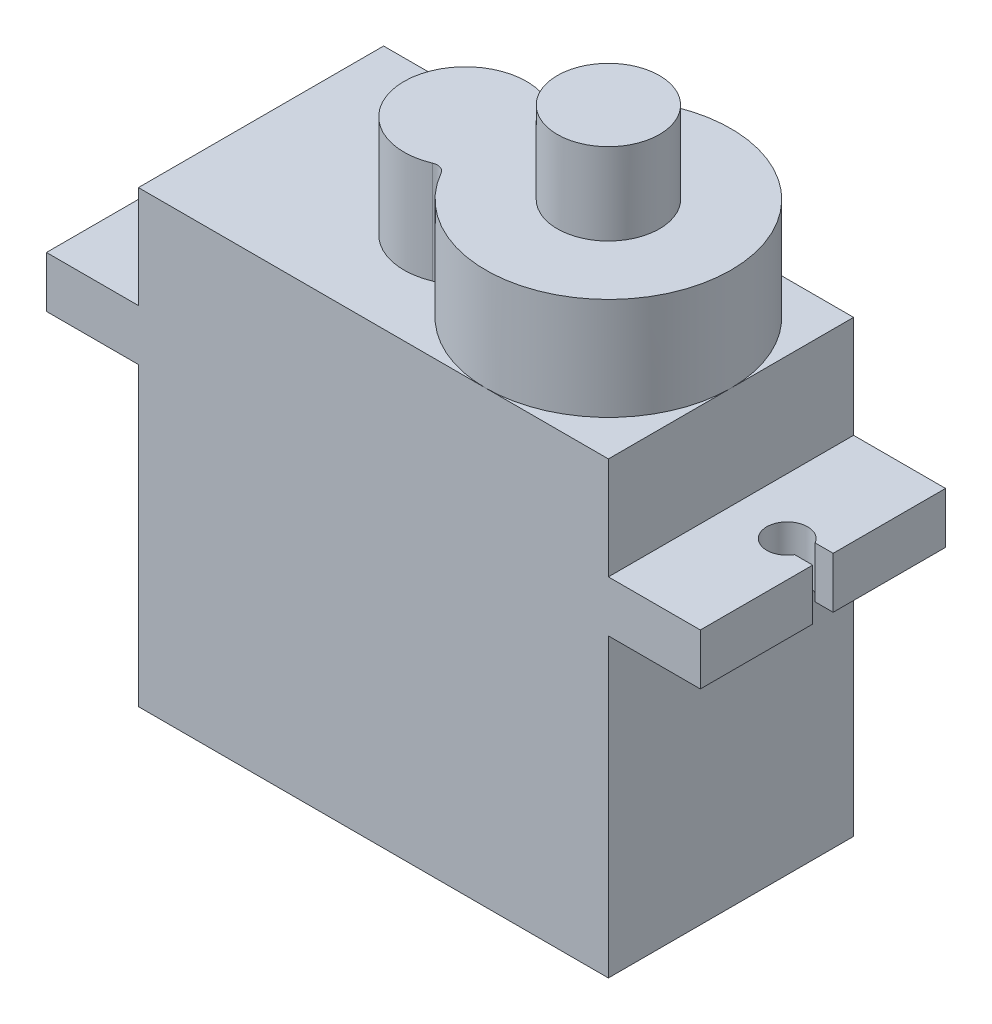
SolidWorks part; units mm, degrees
ref_plane "前视基准面" through (0, 0, 0) normal (0, 0, 1) x (1, 0, 0)
ref_plane "上视基准面" through (0, 0, 0) normal (0, 1, 0) x (1, 0, 0)
ref_plane "右视基准面" through (0, 0, 0) normal (1, 0, 0) x (0, 0, -1)
sketch "草图1" plane through (0, 0, 0) normal (0, 1, 0) x (1, 0, 0)
  line L1 (-11.5, -6) -> (11.5, -6)
  line L2 (-11.5, -6) -> (-11.5, 6)
  line L3 (-11.5, 6) -> (11.5, 6)
  line L4 (11.5, -6) -> (11.5, 6)
  line L5 (0, 6) -> (0, -6) construction
  line L6 (-11.5, 0) -> (11.5, 0) construction
  point P0 (0, 0)
  dimension "D1" = 12
  dimension "D2" = 23
extrude "凸台-拉伸1" add sketch "草图1" along normal blind 22
ref_plane "基准面1" through (0, 17, 0) normal (0, 1, 0) x (1, 0, 0)
sketch "草图2" plane through (0, 17, 0) normal (0, 1, 0) x (1, 0, 0)
  line L0 (-11.5, -6) -> (11.5, -6) construction
  line L1 (-16, -6) -> (16, -6)
  line L2 (-16, -6) -> (-16, 6)
  line L3 (-16, 6) -> (16, 6)
  line L4 (16, -6) -> (16, 6)
  line L5 (0, 6) -> (0, -6) construction
  line L6 (-16, 0) -> (16, 0) construction
  point P0 (0, 0)
  dimension "D1" = 32
extrude "凸台-拉伸2" add sketch "草图2" against normal blind 2.5
sketch "草图3" plane through (0, 17, 0) normal (0, 1, 0) x (1, 0, 0)
  line L0 (-16, 6) -> (-16, -6) construction
  line L1 (-16, 0.5) -> (-15.116, 0.5)
  line L2 (-16, 0.5) -> (-16, -0.5)
  line L3 (-16, -0.5) -> (-15.116, -0.5)
  line L5 (-15.558, -0.5) -> (-15.558, 0.5) construction
  line L6 (-16, 0) -> (-15.558, 0) construction
  arc A0 (-15.116, -0.5) -> (-15.116, 0.5) centre (-14.25, 0) ccw
  point P363 (-15.558, 0)
  dimension "D1" = 2
  dimension "D3" = 1.75
extrude "切除-拉伸1" cut sketch "草图3" against normal through all
mirror "镜向1" about plane through (0, 0, 0) normal (1, 0, 0) of "切除-拉伸1"
sketch "草图4" plane through (0, 22, 0) normal (0, 1, 0) x (1, 0, 0)
  line L0 (-11.5, -6) -> (11.5, -6) construction
  line L1 (11.5, -6) -> (11.5, 6) construction
  line L2 (-11.5, 6) -> (-11.5, -6) construction
  arc A0 (0.2912, -2.978) -> (0.2912, 2.978) centre (5.5, 0) ccw
  arc A1 (-0.3367, 2.7653) -> (-0.3367, -2.7653) centre (-1.5, 0) ccw
  arc A2 (-0.3367, -2.7653) -> (0.2912, -2.978) centre (-0.1429, -3.2262) cw
  arc A3 (-0.3367, 2.7653) -> (0.2912, 2.978) centre (-0.1429, 3.2262) ccw
  dimension "D1" = 6
  dimension "D3" = 0.5
  dimension "D2" = 10
extrude "凸台-拉伸3" add sketch "草图4" along normal blind 5
sketch "草图5" plane through (0, 27, 0) normal (0, 1, 0) x (1, 0, 0)
  circle A0 centre (5.5, 0) radius 2.5
  dimension "D1" = 5
extrude "凸台-拉伸4" add sketch "草图5" along normal blind 4
sketch "草图6" plane through (0, 17, 0) normal (0, 1, 0) x (1, 0, 0)
  line L0 (-16, 6) -> (-16, -6)
  line L1 (-16, -6) -> (-16, 0)
  line L2 (-16, 0) -> (-13.25, 0)
  line L3 (-13.25, 0) -> (-14.25, 0)
  line L4 (-14.25, 0) -> (-16, 0)
  line L5 (-14.25, 0) -> (-11.5, 0)
  line L6 (-11.5, -6) -> (-11.5, 6) construction
  arc A0 (-15.116, -0.5) -> (-15.116, 0.5) centre (-14.25, 0) ccw construction
  dimension "D1" = 1.75
sketch "草图7" plane through (0, 0, 6) normal (0, 0, 1) x (1, 0, 0)
  line L0 (5.5, 31) -> (5.5, 0)
  line L1 (8, 31) -> (3, 31) construction
  line L2 (-11.5, 0) -> (11.5, 0) construction
  line L3 (5.5, 0) -> (5.5, 31)
  line L4 (-11.5, 0) -> (11.5, 0) construction
sketch "草图8" plane through (0, 0, 0) normal (0, -1, 0) x (1, 0, 0)
  line L0 (-11.5, 6) -> (11.5, 6)
  line L1 (-16, -0.5) -> (-16, 0.5)
  line L2 (-16, 0.5) -> (-16, 0)
  line L3 (-16, 0) -> (-14.25, 0)
  line L4 (-14.25, 0) -> (-11.5, 0)
  line L5 (-11.5, 6) -> (-11.5, -6) construction
  line L6 (-14.25, 0) -> (14.25, 0)
  line L7 (-14.25, 0) -> (-14.25, 6)
  line L8 (-16, 6) -> (-11.5, 6) construction
  dimension "D1" = 6
sketch "草图9" plane through (0, 0, -6) normal (0, 0, -1) x (-1, 0, 0)
  line L0 (-5.5, 31) -> (-5.5, 0)
  line L1 (-3, 31) -> (-8, 31) construction
  line L2 (-11.5, 0) -> (11.5, 0) construction
  line L3 (16, 17) -> (-16, 17)
sketch "草图10" plane through (11.5, 0, 0) normal (1, 0, 0) x (0, 0, -1)
  line L0 (-6, 14.5) -> (6, 14.5)
sketch "草图11" plane through (0, 0, 6) normal (0, 0, 1) x (1, 0, 0)
  line L0 (-16, 14.5) -> (-11.5, 14.5)
  line L1 (-11.5, 14.5) -> (-11.5, 0)
  line L2 (-11.5, 0) -> (11.5, 0)
  line L3 (11.5, 0) -> (19.3362, 10.2996)
  line L4 (-11.5, 14.5) -> (-11.5, 0)
  dimension "D1" = 4.5
  dimension "D2" = 23
  dimension "D3" = 14.5
